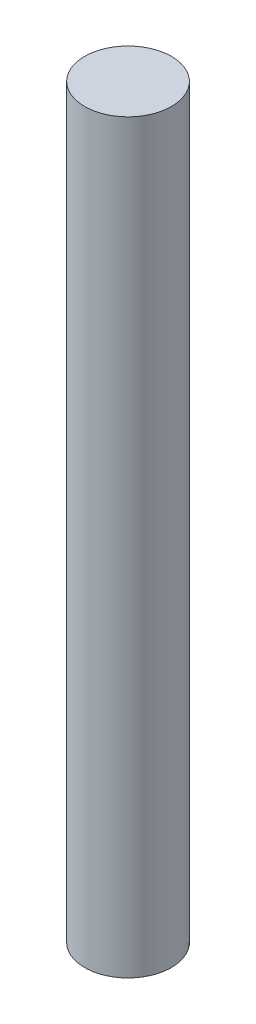
SolidWorks part; units mm, degrees
ref_plane "Front Plane" through (0, 0, 0) normal (0, 0, 1) x (1, 0, 0)
ref_plane "Top Plane" through (0, 0, 0) normal (0, 1, 0) x (1, 0, 0)
ref_plane "Right Plane" through (0, 0, 0) normal (1, 0, 0) x (0, 0, -1)
sketch "Sketch1" plane through (0, 0, 0) normal (0, 1, 0) x (1, 0, 0)
  circle A0 centre (0, 0) radius 10.795
  dimension "D1" = 21.59
extrude "Boss-Extrude1" add sketch "Sketch1" along normal blind 185.42
